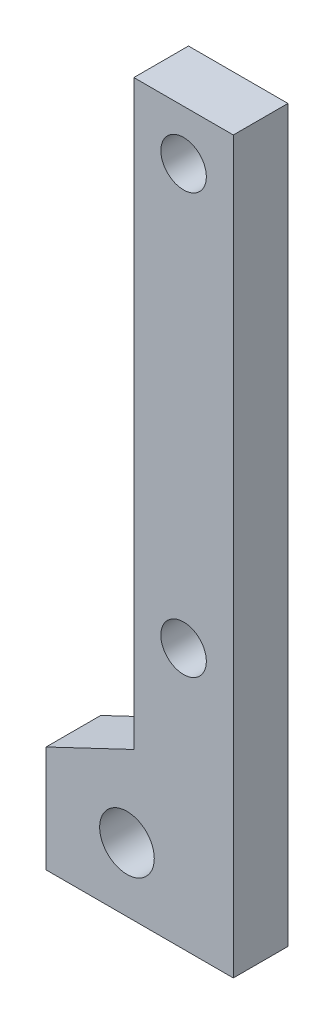
SolidWorks part; units mm, degrees
material "ABS PC"
ref_plane "Front Plane" through (0, 0, 0) normal (0, 0, 1) x (1, 0, 0)
ref_plane "Top Plane" through (0, 0, 0) normal (0, 1, 0) x (1, 0, 0)
ref_plane "Right Plane" through (0, 0, 0) normal (1, 0, 0) x (0, 0, -1)
sketch "Sketch1" plane through (0, 0, 0) normal (0, 0, 1) x (1, 0, 0)
  line L0 (-28.6701, 11.1701) -> (-31.4017, 11.1701) construction
  line L1 (-31.4017, 13.9017) -> (-25.9385, 13.9017)
  line L2 (-31.4017, 13.9017) -> (-31.4017, -18.0621)
  line L3 (-31.4017, -26.2016) -> (-25.9385, -26.2016)
  line L4 (-25.9385, 13.9017) -> (-25.9385, -26.2016)
  line L5 (-31.4017, -26.2016) -> (-36.2238, -26.2016)
  line L6 (-28.6701, 11.1701) -> (-25.9385, 11.1701) construction
  line L7 (-28.6701, 11.1701) -> (-28.6701, 13.9017) construction
  line L8 (-36.2238, -26.2016) -> (-36.2238, -20.3545)
  line L9 (-36.2238, -20.3545) -> (-31.4017, -18.0621)
  line L10 (-71.78, -18.0621) -> (43.22, -18.0621) construction
  circle A0 centre (-28.6701, 11.1701) radius 1.25
  circle A1 centre (-28.6701, -11.8799) radius 1.25
  arc A2 (-28.75, 15) -> (-32.5, 11.25) centre (-28.75, 11.25) ccw construction
  circle A3 centre (-31.78, -22.6939) radius 1.5
  circle A4 centre (-31.78, -22.6939) radius 1.25 construction
  dimension "D2" = 2.5
  dimension "D4" = 3
  dimension "D1" = 23.05
  dimension "D3" = 5.4632
extrude "Boss-Extrude1" add sketch "Sketch1" along normal blind 3
sketch "Bend-Lines1" [suppressed] plane through (0, 0, 0) normal (0, 1, 0) x (1, 0, 0)
sketch "Bounding-Box1" [suppressed] plane through (0, 0, 0) normal (0, 1, 0) x (1, 0, 0)
